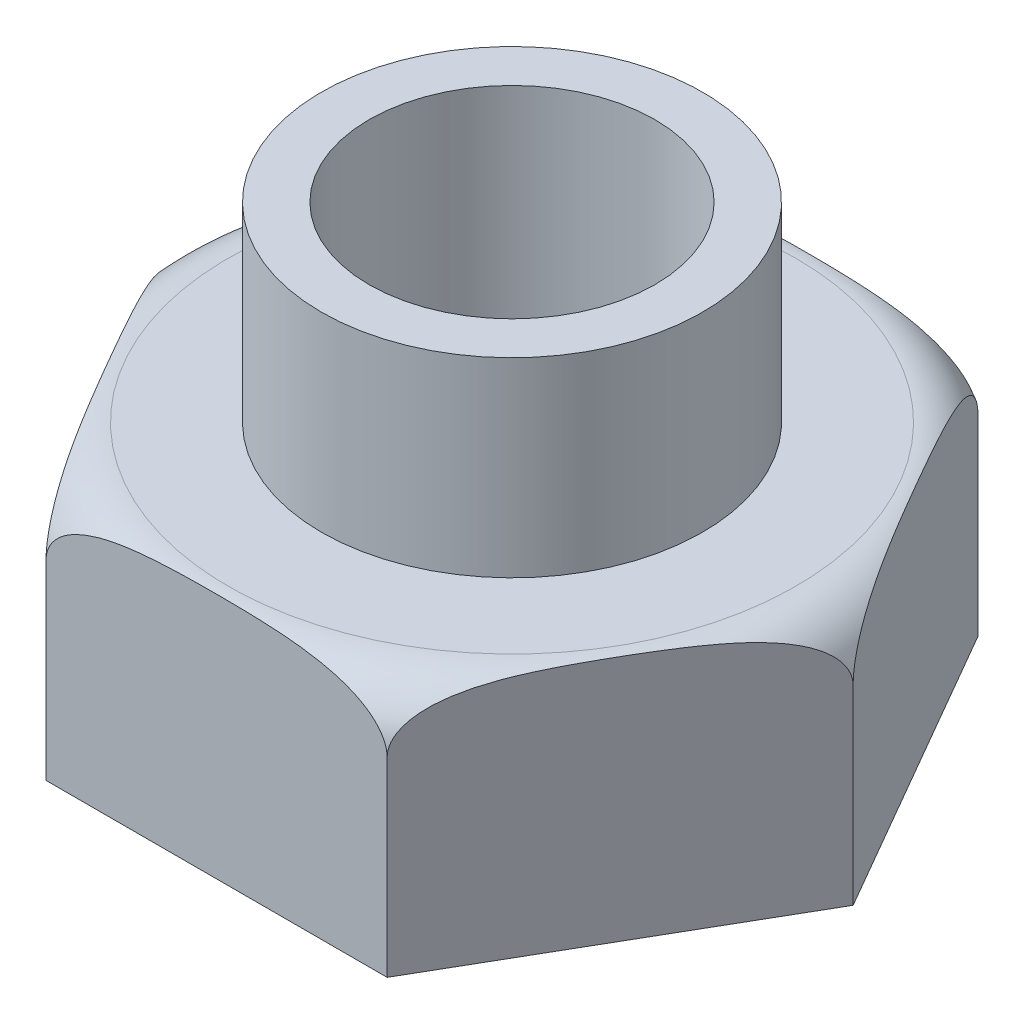
SolidWorks part; units mm, degrees
ref_plane "Front Plane" through (0, 0, 0) normal (0, 0, 1) x (1, 0, 0)
ref_plane "Top Plane" through (0, 0, 0) normal (0, 1, 0) x (1, 0, 0)
ref_plane "Right Plane" through (0, 0, 0) normal (1, 0, 0) x (0, 0, -1)
sketch "Sketch1" plane through (0, 0, 0) normal (0, 1, 0) x (1, 0, 0)
  line L0 (-89.4893, 0) -> (89.4893, 0)
  line L1 (44.7446, 77.5) -> (-44.7446, 77.5)
  line L2 (-44.7446, 77.5) -> (-89.4893, 0)
  line L3 (-89.4893, 0) -> (-44.7446, -77.5)
  line L4 (-44.7446, -77.5) -> (44.7446, -77.5)
  line L5 (44.7446, -77.5) -> (89.4893, 0)
  line L6 (89.4893, 0) -> (44.7446, 77.5)
  circle A0 centre (0, 0) radius 77.5 construction
  dimension "D1" = 155
extrude "Boss-Extrude1" add sketch "Sketch1" along normal blind 65 contours L4 L5 L0 L3 | L0 L6 L1 L2
sketch "Sketch2" plane through (0, 0, 0) normal (0, 0, 1) x (1, 0, 0)
  line L0 (0, 0) -> (0, 75.4255)
  line L2 (44.7446, 65) -> (89.4893, 65) construction
  line L5 (89.4893, 65) -> (89.4893, 0) construction
  line L7 (74.4893, 65) -> (74.4893, 71.0339)
  line L8 (74.4893, 71.0339) -> (95.9092, 71.0339)
  line L9 (95.9092, 71.0339) -> (95.9092, 50)
  line L10 (95.9092, 50) -> (89.4893, 50)
  line L11 (74.4893, 65) -> (74.4893, 50) construction
  line L12 (74.4893, 50) -> (89.4893, 50) construction
  arc A0 (74.4893, 65) -> (89.4893, 50) centre (74.4893, 50) cw
  point P5 (0, 0)
  point P15 (95.9092, 71.0339)
  dimension "D1" = 15
revolve "Cut-Revolve1" cut sketch "Sketch2" angle 360 about L0
sketch "Sketch4" plane through (0, 65, 0) normal (0, 1, 0) x (1, 0, 0)
  circle A0 centre (0, 0) radius 50
  dimension "D1" = 100
extrude "Boss-Extrude2" add sketch "Sketch4" along normal blind 50 contours A0
sketch "Sketch5" plane through (0, 115, 0) normal (0, 1, 0) x (1, 0, 0)
  circle A0 centre (0, 0) radius 37.5
  dimension "D1" = 75
extrude "Cut-Extrude1" cut sketch "Sketch5" against normal through all both
